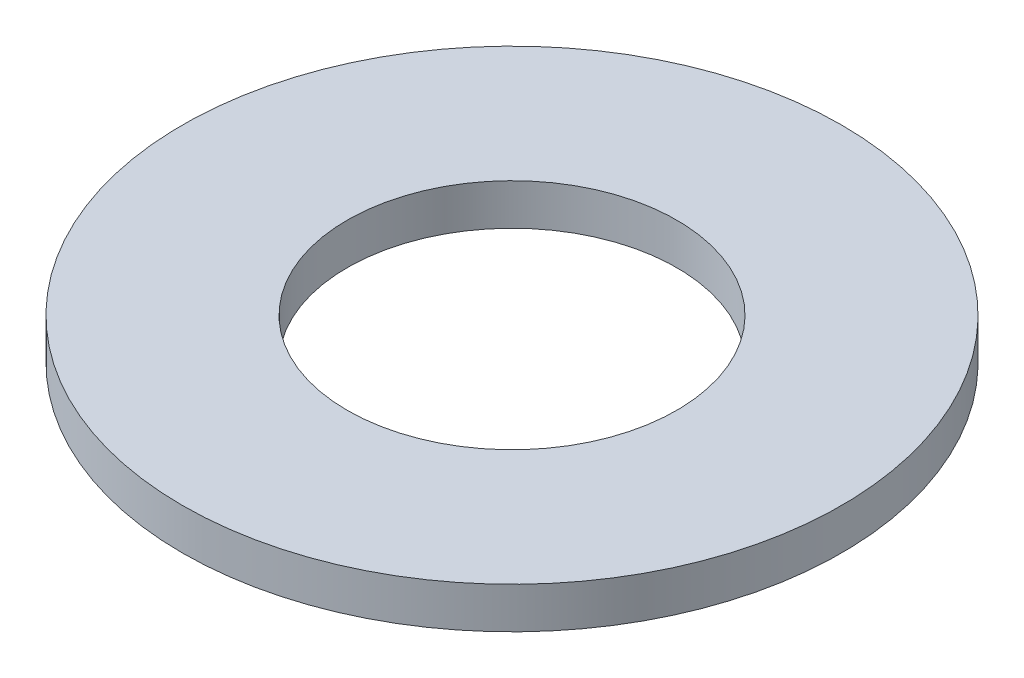
SolidWorks part; units mm, degrees
ref_plane "Front Plane" through (0, 0, 0) normal (0, 0, 1) x (1, 0, 0)
ref_plane "Top Plane" through (0, 0, 0) normal (0, 1, 0) x (1, 0, 0)
ref_plane "Right Plane" through (0, 0, 0) normal (1, 0, 0) x (0, 0, -1)
sketch "Sketch1" plane through (0, 0, 0) normal (0, 1, 0) x (1, 0, 0)
  circle A0 centre (0, 0) radius 6.35
  dimension "D1" = 12.7
extrude "Boss-Extrude1" add sketch "Sketch1" along normal blind 0.7937
sketch "Sketch2" plane through (0, 0.7937, 0) normal (0, 1, 0) x (1, 0, 0)
  circle A0 centre (0, 0) radius 3.175
  dimension "D1" = 6.35
extrude "Cut-Extrude1" cut sketch "Sketch2" against normal blind 17.4625
